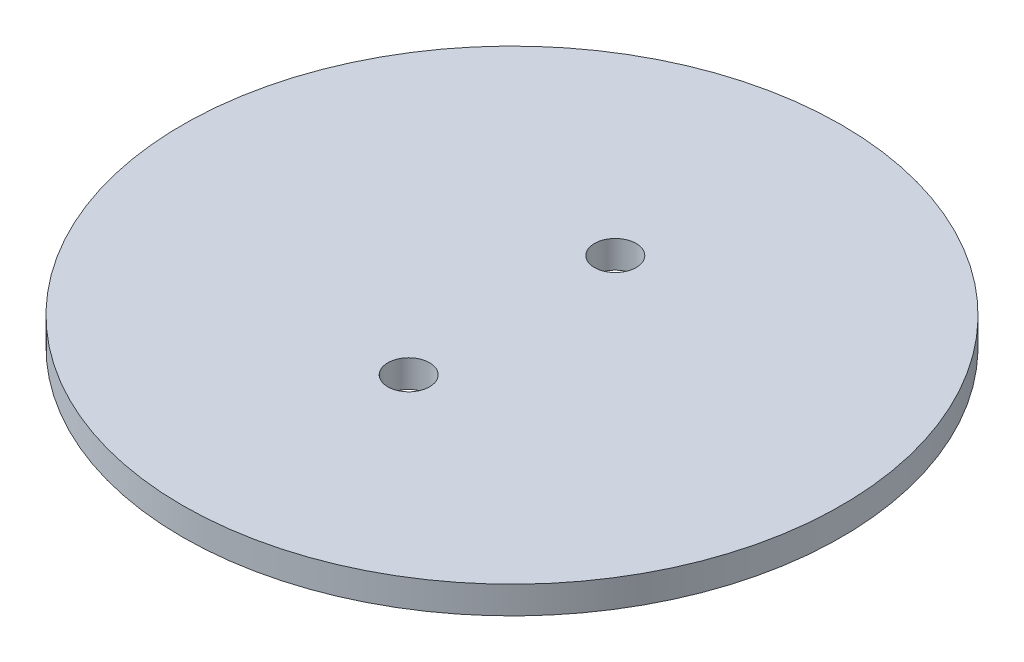
SolidWorks part; units mm, degrees
material "E-Glass Fiber"
ref_plane "Front Plane" through (0, 0, 0) normal (0, 0, 1) x (1, 0, 0)
ref_plane "Top Plane" through (0, 0, 0) normal (0, 1, 0) x (1, 0, 0)
ref_plane "Right Plane" through (0, 0, 0) normal (1, 0, 0) x (0, 0, -1)
sketch "Sketch1" plane through (0, 0, 0) normal (0, 1, 0) x (1, 0, 0)
  circle A0 centre (0, 0) radius 76.1746
  dimension "D1" = 152.3492
extrude "Boss-Extrude1" add sketch "Sketch1" along normal blind 6.35
sketch "Sketch2" plane through (0, 6.35, 0) normal (0, 1, 0) x (1, 0, 0)
  circle A0 centre (0, 23.876) radius 4.826
  circle A1 centre (0, -23.876) radius 4.826
  dimension "D1" = 9.652
  dimension "D2" = 9.652
  dimension "D3" = 47.752
  dimension "D4" = 23.876
extrude "Cut-Extrude1" cut sketch "Sketch2" against normal blind 18.796
